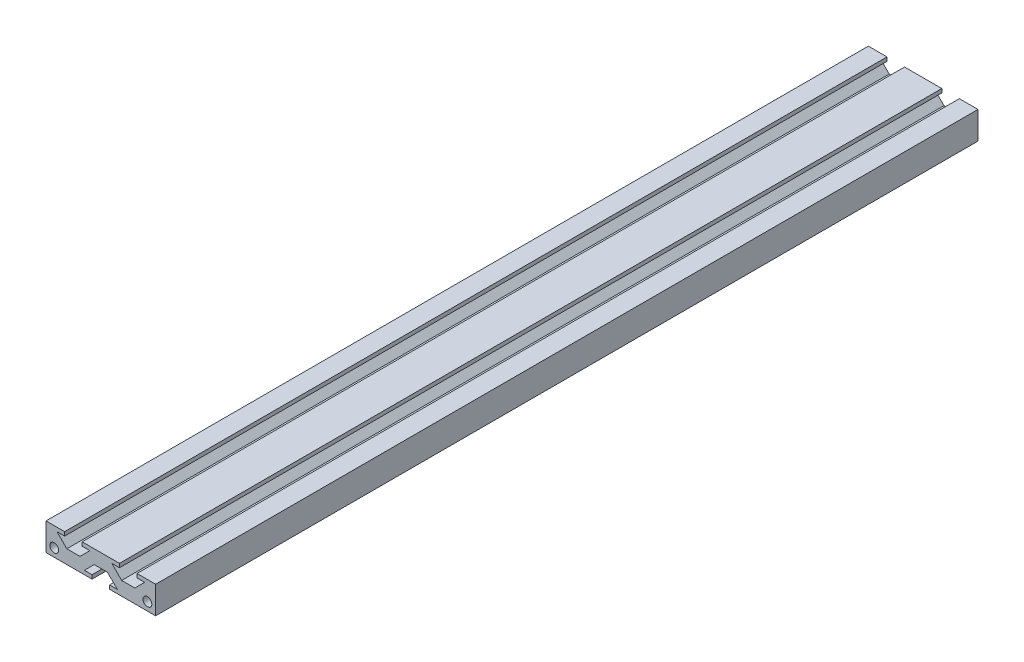
SolidWorks part; units mm, degrees
ref_plane "Front Plane" through (0, 0, 0) normal (0, 0, 1) x (1, 0, 0)
ref_plane "Top Plane" through (0, 0, 0) normal (0, 1, 0) x (1, 0, 0)
ref_plane "Right Plane" through (0, 0, 0) normal (1, 0, 0) x (0, 0, -1)
sketch "Sketch1" plane through (0, 0, 0) normal (0, 0, 1) x (1, 0, 0)
  line L0 (-13.2, 5) -> (-13.2, 3.6)
  line L1 (20, 5) -> (13.2, 5)
  line L2 (20, 5) -> (20, -5)
  line L3 (20, -5) -> (3.2, -5)
  line L4 (-20, 5) -> (-20, -5)
  line L5 (20, 5) -> (-20, -5) construction
  line L6 (20, -5) -> (-20, 5) construction
  line L7 (-13.2, 3.6) -> (-16, 3.6)
  line L8 (-16, 3.6) -> (-12.4, 0)
  line L9 (-12.4, 0) -> (-7.6, 0)
  line L10 (-7.6, 0) -> (-4, 3.6)
  line L11 (-4, 3.6) -> (-6.8, 3.6)
  line L12 (-6.8, 3.6) -> (-6.8, 5)
  line L14 (-13.2, 5) -> (-20, 5)
  line L15 (6.8, 5) -> (6.8, 3.6)
  line L16 (6.8, 3.6) -> (4, 3.6)
  line L17 (4, 3.6) -> (7.6, 0)
  line L18 (7.6, 0) -> (12.4, 0)
  line L19 (12.4, 0) -> (16, 3.6)
  line L20 (16, 3.6) -> (13.2, 3.6)
  line L21 (13.2, 3.6) -> (13.2, 5)
  line L22 (6.8, 5) -> (-6.8, 5)
  line L23 (3.2, -5) -> (3.2, -3.6)
  line L24 (3.2, -3.6) -> (6, -3.6)
  line L25 (6, -3.6) -> (2.4, 0)
  line L26 (2.4, 0) -> (-2.4, 0)
  line L27 (-2.4, 0) -> (-6, -3.6)
  line L28 (-6, -3.6) -> (-3.2, -3.6)
  line L29 (-3.2, -3.6) -> (-3.2, -5)
  line L30 (-3.2, -5) -> (-20, -5)
  circle A0 centre (-17, -2) radius 1.6
  circle A1 centre (17, -2) radius 1.6
  point P0 (0, 0)
  point P8 (-10, 0)
  dimension "D8" = 3.2
  dimension "D10" = 3
  dimension "D1" = 40
  dimension "D2" = 10
  dimension "D3" = 6.4
  dimension "D4" = 12
  dimension "D5" = 45
  dimension "D6" = 1.4
  dimension "D7" = 10
  dimension "D9" = 3
  dimension "D11" = 3
  dimension "D12" = 2
extrude "Boss-Extrude1" add sketch "Sketch1" along normal blind 300
